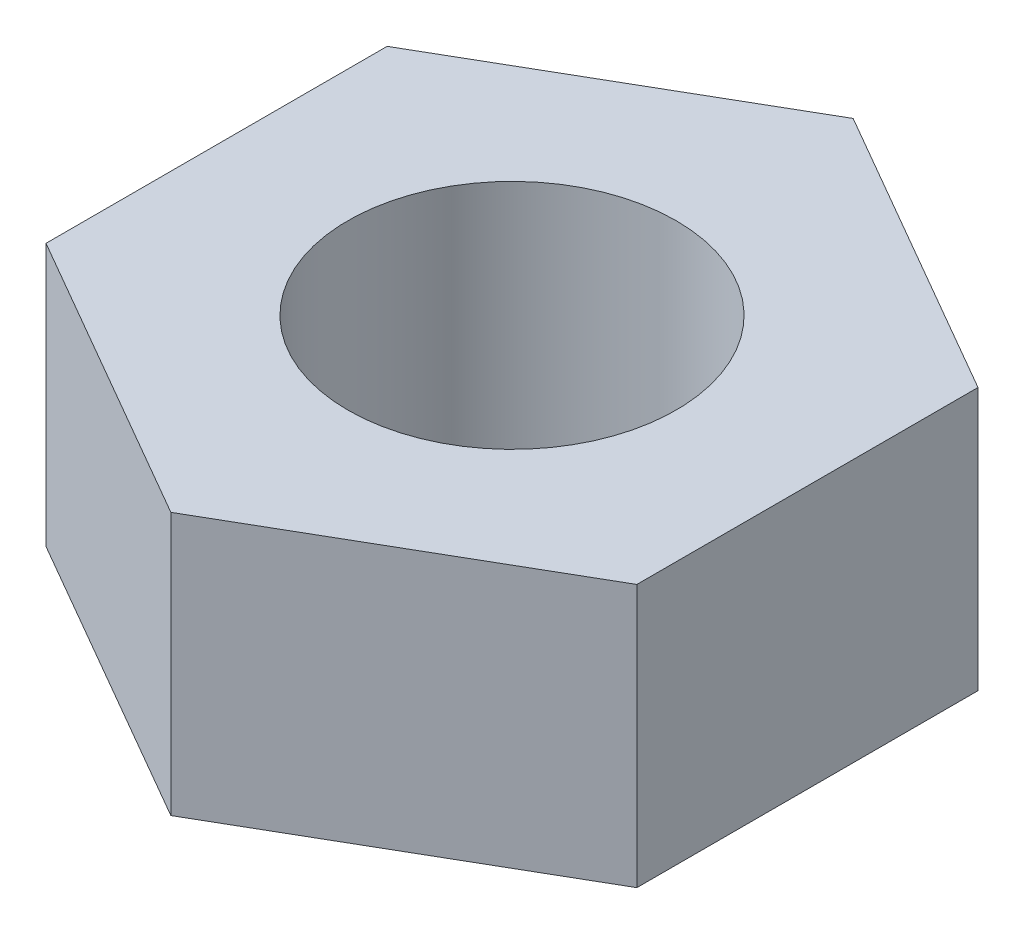
SolidWorks part; units mm, degrees
ref_plane "Front Plane" through (0, 0, 0) normal (0, 0, 1) x (1, 0, 0)
ref_plane "Top Plane" through (0, 0, 0) normal (0, 1, 0) x (1, 0, 0)
ref_plane "Right Plane" through (0, 0, 0) normal (1, 0, 0) x (0, 0, -1)
sketch "Sketch1" plane through (0, 0, 0) normal (0, 1, 0) x (1, 0, 0)
  line L1 (0, 3.1177) -> (-2.7, 1.5588)
  line L2 (-2.7, 1.5588) -> (-2.7, -1.5588)
  line L3 (-2.7, -1.5588) -> (0, -3.1177)
  line L4 (0, -3.1177) -> (2.7, -1.5588)
  line L5 (2.7, -1.5588) -> (2.7, 1.5588)
  line L6 (2.7, 1.5588) -> (0, 3.1177)
  circle A0 centre (0, 0) radius 2.7 construction
  circle A1 centre (0, 0) radius 1.5
  dimension "D1" = 5.4
  dimension "D2" = 3
extrude "Boss-Extrude1" add sketch "Sketch1" along normal blind 2.4
